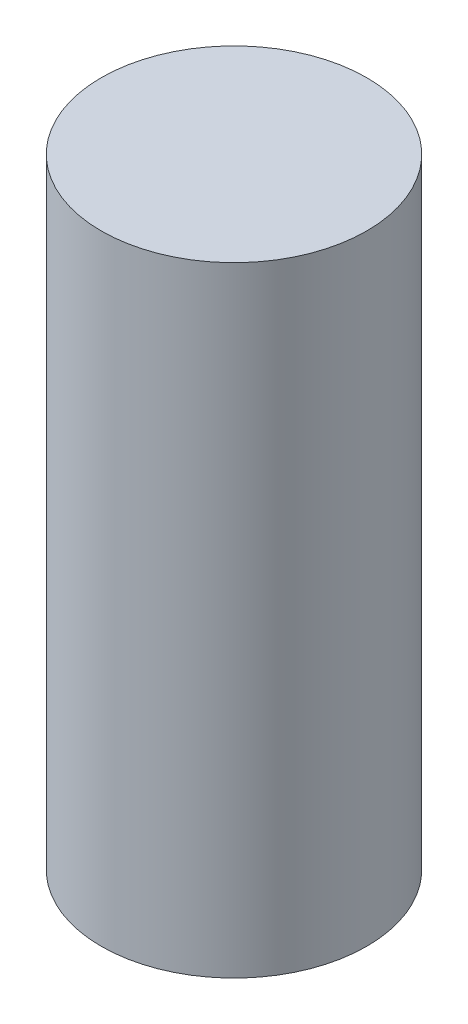
SolidWorks part; units mm, degrees
material "1060 Alloy"
ref_plane "Front Plane" through (0, 0, 0) normal (0, 0, 1) x (1, 0, 0)
ref_plane "Top Plane" through (0, 0, 0) normal (0, 1, 0) x (1, 0, 0)
ref_plane "Right Plane" through (0, 0, 0) normal (1, 0, 0) x (0, 0, -1)
sketch "Sketch1" plane through (0, 0, 0) normal (0, 1, 0) x (1, 0, 0)
  circle A0 centre (0, 0) radius 7.5
  dimension "D1" = 15
extrude "Boss-Extrude1" add sketch "Sketch1" along normal blind 35
